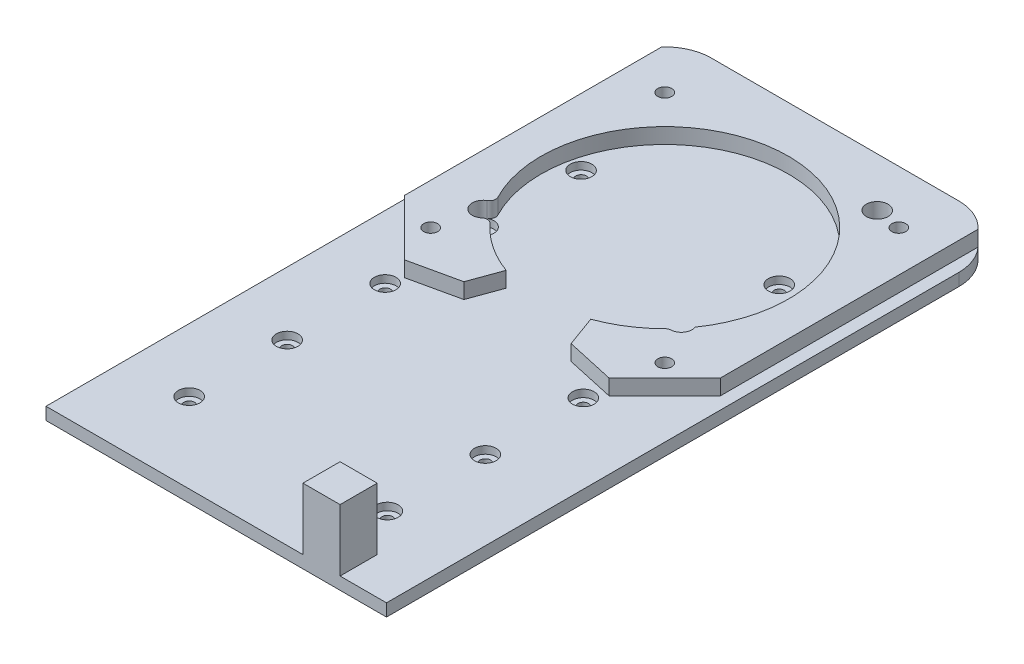
SolidWorks part; units mm, degrees
ref_plane "Plan de face" through (0, 0, 0) normal (0, 0, 1) x (1, 0, 0)
ref_plane "Plan de dessus" through (0, 0, 0) normal (0, 1, 0) x (1, 0, 0)
ref_plane "Plan de droite" through (0, 0, 0) normal (1, 0, 0) x (0, 0, -1)
sketch "Esquisse1" plane through (0, 0, 0) normal (0, 0, 1) x (1, 0, 0)
  line L3 (55.0272, 0) -> (55.0272, -4)
  line L8 (-55.0272, -4) -> (-55.0272, 0)
  line L9 (-55.0272, 0) -> (55.0272, 0)
  line L10 (55.0272, -4) -> (-55.0272, -4)
  point P18 (0, 0)
  dimension "D2" = 4
  dimension "D1" = 110.0544
extrude "Boss.-Extru.1" add sketch "Esquisse1" along normal mid plane 200
hole_wizard "Chambrage pour vis à tête ronde bombée M31" positions "Esquisse8" profile "Esquisse9" counterbore size "M3" standard "Ansi Metric" end condition through all
sketch "Esquisse8" plane through (0, 0, 0) normal (0, -1, 0) x (-1, 0, 0)
  line L0 (-29.4752, -74.1661) -> (-29.4752, -42.4996) construction
  line L1 (-29.4752, -42.4996) -> (-29.4752, -10.833) construction
  line L2 (-29.4752, -10.833) -> (-29.4752, 20.8336) construction
  line L3 (-29.4752, 20.8336) -> (-29.4752, 52.5001) construction
  line L4 (-29.4752, 52.5001) -> (-29.4752, 84.1667) construction
  line L5 (-29.4752, 84.1667) -> (-29.4752, 100) construction
  line L6 (-55.0272, -100) -> (-55.0272, 100) construction
  line L7 (55.0272, 100) -> (-55.0272, 100) construction
  line L8 (34.5802, -74.1661) -> (-29.4752, -74.1661) construction
  line L10 (34.5802, -42.4996) -> (-29.4752, -42.4996) construction
  line L12 (34.5802, -10.833) -> (-29.4752, -10.833) construction
  line L14 (-29.4752, 20.8336) -> (34.5802, 20.8336) construction
  line L16 (34.5802, 84.1667) -> (-29.4752, 84.1667) construction
  line L18 (34.5802, 52.5001) -> (-29.4752, 52.5001) construction
  point P0 (-29.4752, -74.1661)
  point P2 (-29.4752, -42.4996)
  point P4 (-29.4752, -10.833)
  point P6 (-29.4752, 20.8336)
  point P8 (-29.4752, 52.5001)
  point P10 (-29.4752, 84.1667)
  point P14 (34.5802, 52.5001)
  point P16 (34.5802, 20.8336)
  point P18 (34.5802, -10.833)
  point P20 (34.5802, -42.4996)
  point P22 (34.5802, -74.1661)
  dimension "D1" = 15.8333
  dimension "D2" = 25.552
  dimension "D3" = 31.6666
  dimension "D4" = 64.0555
sketch "Esquisse9" plane through (29.4752, 0, 74.1661) normal (1, 0, 0) x (0, 0, 1)
  line L0 (0, 0) -> (0, 4)
  line L1 (0, 4) -> (1.7, 4)
  line L3 (1.7, 4) -> (1.7, 2.4)
  line L4 (1.7, 2.4) -> (3.5, 2.4)
  line L5 (3.5, 2.4) -> (3.5, 0)
  line L7 (3.5, 0) -> (0, 0)
  line L11 (0, -6.35) -> (0, 107.95) construction
  dimension "Diamètre du perçage jusqu'au prochain" = 3.4
  dimension "Profondeur du perçage jusqu'au prochain" = 4
  dimension "Diamètre du chambrage" = 7
  dimension "Profondeur du chambrage" = 2.4
sketch "Esquisse2" plane through (0, 0, 0) normal (0, 1, 0) x (1, 0, 0)
  line L0 (-0.0272, 45) -> (42.0425, 2.924) construction
  line L1 (-0.0272, 45) -> (0, 0) construction
  line L9 (-0.0272, 45) -> (-10.8441, 45) construction
  line L17 (-51.1123, 11.9424) -> (-33.0891, -6.0836)
  line L18 (-33.0891, -6.0836) -> (-17.3519, -2.596)
  line L19 (-17.3519, -2.596) -> (-13.7083, 7.4124)
  line L25 (47.5688, 27.6753) -> (37.5604, 31.3189) construction
  line L26 (51.0564, 11.9381) -> (47.5688, 27.6753) construction
  line L27 (33.0304, -6.0851) -> (51.0564, 11.9381)
  line L28 (17.2932, -2.5975) -> (33.0304, -6.0851)
  line L29 (13.6496, 7.4109) -> (17.2932, -2.5975)
  line L36 (-51.1123, 11.9424) -> (-51.1123, 100)
  line L37 (-51.1123, 100) -> (51.0564, 100)
  line L38 (55.0272, 100) -> (-55.0272, 100) construction
  line L39 (-33.0848, 96.0851) -> (-51.1108, 78.0619) [skipped]
  line L40 (-47.6232, 62.3247) -> (-37.6148, 58.6811) [skipped]
  line L41 (-51.1108, 78.0619) -> (-47.6232, 62.3247) [skipped]
  line L42 (-13.704, 82.5891) -> (-17.3477, 92.5975) [skipped]
  line L43 (-17.3477, 92.5975) -> (-33.0848, 96.0851) [skipped]
  line L44 (17.2975, 92.596) -> (13.6539, 82.5876) [skipped]
  line L45 (37.5619, 58.6768) -> (47.5703, 62.3205) [skipped]
  line L46 (33.0347, 96.0836) -> (17.2975, 92.596) [skipped]
  line L47 (51.0564, 100) -> (51.0564, 11.9381)
  line L49 (51.0564, 78.0506) -> (51.0579, 78.0576) [skipped]
  line L50 (51.0579, 78.0576) -> (51.0564, 78.0592) [skipped]
  line L51 (-37.6164, 31.3232) -> (-47.6247, 27.6795) [skipped]
  line L52 (-47.6247, 27.6795) -> (-51.1123, 11.9424) [skipped]
  circle A12 centre (29.4752, 20.8336) radius 3.5 construction
  arc A13 (28.9062, 17.3801) -> (32.749, 22.0714) centre (29.4752, 20.8336) ccw
  arc A14 (13.6496, 7.4109) -> (28.9062, 17.3801) centre (-0.0272, 45) ccw
  circle A18 centre (-34.5802, 20.8336) radius 3.5 construction
  arc A19 (-34.2663, 24.3194) -> (-31.1982, 19.9327) centre (-34.5802, 20.8336) ccw
  arc A20 (-31.1982, 19.9327) -> (-13.7083, 7.4124) centre (-0.0272, 45) ccw
  arc A22 (-13.704, 82.5891) -> (-37.6148, 58.6811) centre (-0.0272, 45) ccw [skipped]
  arc A23 (37.5619, 58.6768) -> (13.6539, 82.5876) centre (-0.0272, 45) ccw [skipped]
  arc A24 (-31.1982, 19.9327) -> (-13.7083, 7.4124) centre (-0.0272, 45) ccw
  arc A25 (13.6496, 7.4109) -> (28.9062, 17.3801) centre (-0.0272, 45) ccw
  arc A26 (-37.6164, 31.3232) -> (-34.2663, 24.3194) centre (-0.0272, 45) ccw [skipped]
  arc A27 (13.6496, 7.4109) -> (28.9062, 17.3801) centre (-0.0272, 45) ccw
  arc A28 (32.749, 22.0714) -> (37.5604, 31.3189) centre (-0.0272, 45) ccw
  arc A29 (32.749, 22.0714) -> (37.5604, 31.3189) centre (-0.0272, 45) ccw
  arc A30 (32.749, 22.0714) -> (-13.7083, 7.4124) centre (-0.0272, 45) ccw
  point P38 (-0.0272, 45)
  dimension "D5" = 25.4906
  dimension "D6" = 122.509
  dimension "D11" = 40
  dimension "D1" = 55
  dimension "D2" = 55.0544
  dimension "D3" = 44.961
  dimension "D4" = 59.5
  dimension "D7" = 122.5
  dimension "D8" = 122.5
  dimension "D9" = 122.5
  dimension "D10" = 42.8141
  dimension "D12" = 102.1687
  dimension "D13" = 4
extrude "Boss.-Extru.2" add sketch "Esquisse2" along normal blind 5
fillet "Congé1" radius 15 2 edges at (55.0272, -2, -100) (-55.0272, -2, -100)
hole_wizard "Diamètre du perçage Ø4.5 (4.5)1" positions "Esquisse10" profile "Esquisse11" hole size "Ø4.5" standard "Ansi Metric" end condition through all
sketch "Esquisse10" plane through (0, 5, 0) normal (0, 1, 0) x (1, 0, 0)
  line L0 (-0.0272, 45) -> (37.8059, 7.1726) construction
  line L2 (0, 0) -> (-0.0272, 45) construction
  point P0 (37.8059, 7.1726)
  dimension "D1" = 44.97
  dimension "D2" = 53.5
sketch "Esquisse11" plane through (37.8059, 5, -7.1726) normal (1, 0, 0) x (0, 0, 1)
  line L0 (0, 0) -> (0, 9)
  line L1 (0, 9) -> (2.25, 9)
  line L2 (2.25, 9) -> (2.25, 0)
  line L5 (2.25, 0) -> (0, 0)
  line L11 (0, -6.35) -> (0, 107.95) construction
  dimension "Diamètre du perçage jusqu'au prochain" = 4.5
  dimension "Profondeur du perçage jusqu'au prochain" = 9
pattern_circular "Répétition circulaire1" count 4 over 360 about axis through (-0.0272, 0, -45) along (0, 1, 0) of "Diamètre du perçage Ø4.5 (4.5)1"
fillet "Congé2" radius 2 3 edges at (28.9062, 2.5, -17.3801) (-34.2663, 2.5, -24.3194) (-31.1982, 2.5, -19.9327)
sketch "Esquisse12" plane through (0, 0, 0) normal (0, 1, 0) x (1, 0, 0)
  line L0 (40.0272, -100) -> (40.0272, -88)
  line L1 (55.0272, -100) -> (-55.0272, -100) construction
  line L2 (40.0272, -88) -> (28.0272, -88)
  line L3 (28.0272, -88) -> (28.0272, -100)
  line L4 (28.0272, -100) -> (40.0272, -100)
  line L5 (55.0272, -100) -> (55.0272, 85) construction
  point P6 (0, 0)
  point P7 (26.082, -100)
  dimension "D1" = 15
  dimension "D2" = 12
  dimension "D3" = 12
extrude "Boss.-Extru.3" add sketch "Esquisse12" along normal blind 20
